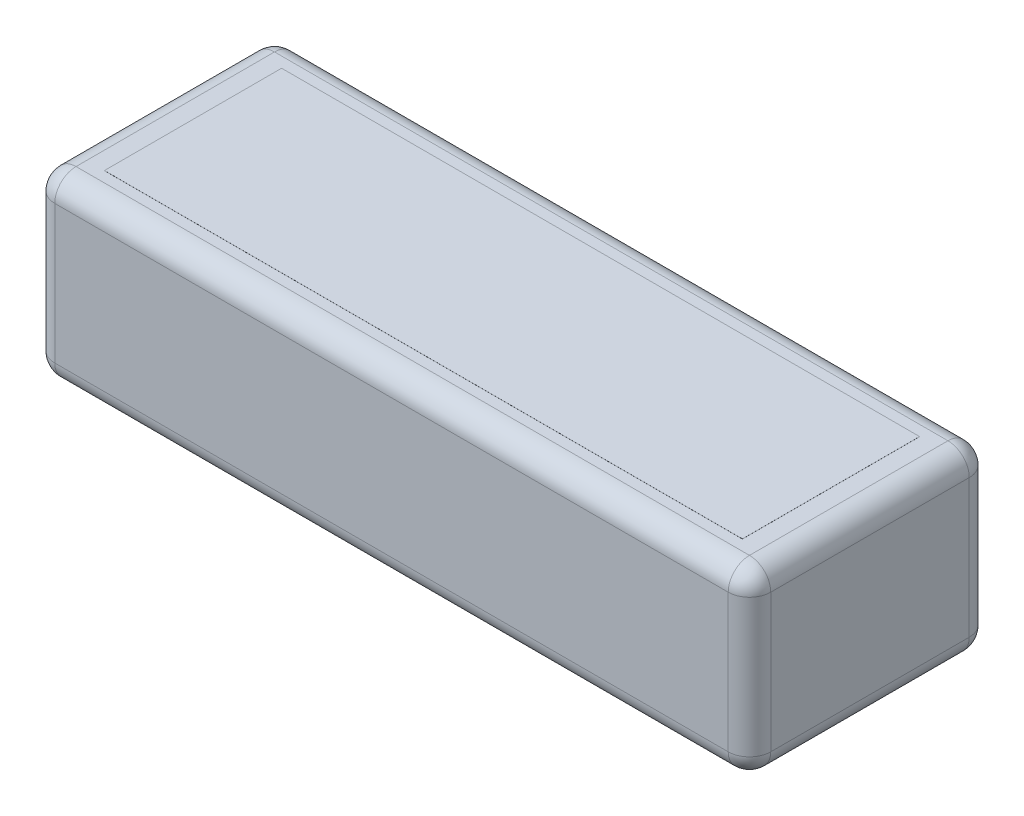
SolidWorks part; units mm, degrees
ref_plane "Front Plane" through (0, 0, 0) normal (0, 0, 1) x (1, 0, 0)
ref_plane "Top Plane" through (0, 0, 0) normal (0, 1, 0) x (1, 0, 0)
ref_plane "Right Plane" through (0, 0, 0) normal (1, 0, 0) x (0, 0, -1)
sketch "Sketch1" plane through (0, 0, 0) normal (0, 1, 0) x (1, 0, 0)
  line L1 (50.5, -17) -> (-50.5, -17)
  line L2 (50.5, -17) -> (50.5, 17)
  line L3 (50.5, 17) -> (-50.5, 17)
  line L4 (-50.5, -17) -> (-50.5, 17)
  line L5 (50.5, -17) -> (-50.5, 17) construction
  line L6 (50.5, 17) -> (-50.5, -17) construction
  point P0 (0, 0)
  dimension "D1" = 101
  dimension "D2" = 34
extrude "Boss-Extrude1" add sketch "Sketch1" along normal blind 25.5
sketch "Sketch2" plane through (0, 25.5, 0) normal (0, 1, 0) x (1, 0, 0)
  line L1 (45, -12.5) -> (-45, -12.5)
  line L2 (45, -12.5) -> (45, 12.5)
  line L3 (45, 12.5) -> (-45, 12.5)
  line L4 (-45, -12.5) -> (-45, 12.5)
  line L5 (45, -12.5) -> (-45, 12.5) construction
  line L6 (45, 12.5) -> (-45, -12.5) construction
  point P0 (0, 0)
  dimension "D1" = 90
  dimension "D2" = 25
extrude "Boss-Extrude2" add sketch "Sketch2" along normal blind 0.01
fillet "Fillet1" radius 3 12 edges at (0, 0, -17) (50.5, 0, 0) (0, 0, 17) (-50.5, 0, 0) (-50.5, 12.75, 17) (-50.5, 12.75, -17) (50.5, 12.75, -17) (50.5, 12.75, 17) (-50.5, 25.5, 0) (0, 25.5, -17) (50.5, 25.5, 0) (0, 25.5, 17)
sketch "Sketch4" plane through (0, 25.51, 0) normal (0, 1, 0) x (1, 0, 0)
  text T0 "<b>LiPo Battery</b>\r\n<b>3000 mAh          20C</b>"
